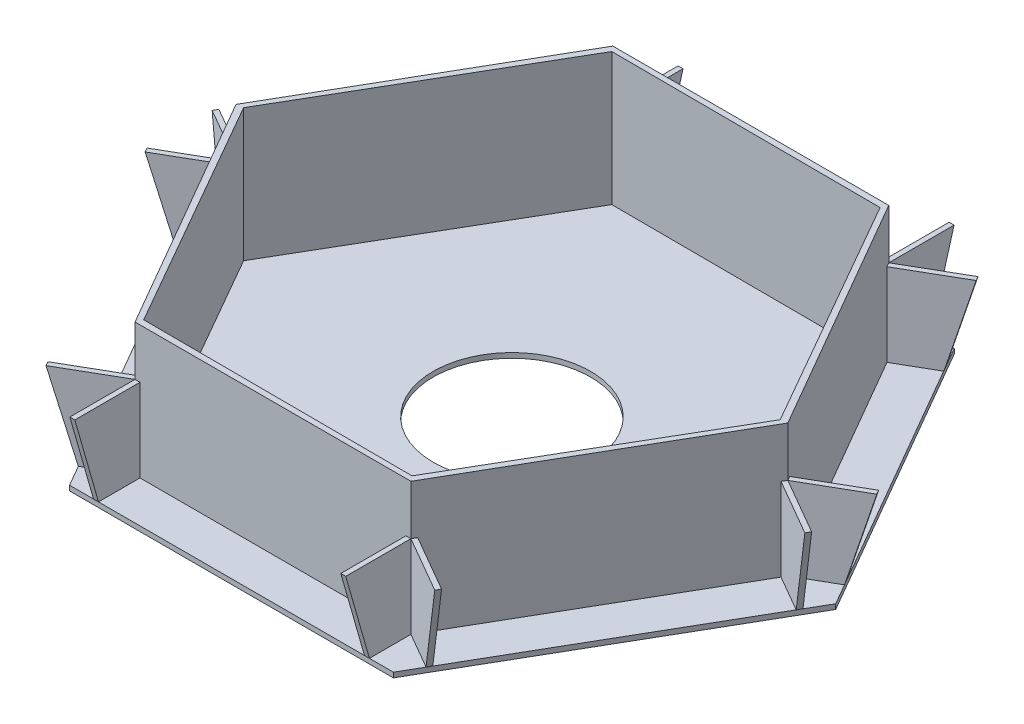
SolidWorks part; units mm, degrees
ref_plane "前视基准面" through (0, 0, 0) normal (0, 0, 1) x (1, 0, 0)
ref_plane "上视基准面" through (0, 0, 0) normal (0, 1, 0) x (1, 0, 0)
ref_plane "右视基准面" through (0, 0, 0) normal (1, 0, 0) x (0, 0, -1)
other "Configuration Table"
sketch "草图3" plane through (0, 0, 0) normal (0, 1, 0) x (1, 0, 0)
  line L1 (195.4, 0) -> (97.7, 169.2214)
  line L2 (97.7, 169.2214) -> (-97.7, 169.2214)
  line L3 (-97.7, 169.2214) -> (-195.4, 0)
  line L4 (-195.4, 0) -> (-97.7, -169.2214)
  line L5 (-97.7, -169.2214) -> (97.7, -169.2214)
  line L6 (97.7, -169.2214) -> (195.4, 0)
  circle A0 centre (0, 0) radius 169.2214 construction
  dimension "D1" = 195.4
extrude "凸台-拉伸2" add sketch "草图3" along normal blind 3
sketch "草图4" plane through (0, 3, 0) normal (0, 1, 0) x (1, 0, 0)
  circle A0 centre (0, 0) radius 47.5
  dimension "D1" = 95
extrude "切除-拉伸1" cut sketch "草图4" against normal blind 3
sketch "草图5" plane through (0, 3, 0) normal (0, 1, 0) x (1, 0, 0)
  line L1 (83.24, 144.1759) -> (-83.24, 144.1759)
  line L2 (-83.24, 144.1759) -> (-166.48, 0)
  line L3 (-166.48, 0) -> (-83.24, -144.1759)
  line L4 (-83.24, -144.1759) -> (83.24, -144.1759)
  line L5 (83.24, -144.1759) -> (166.48, 0)
  line L6 (166.48, 0) -> (83.24, 144.1759)
  line L7 (-80.7295, 141.0053) -> (-162.4789, 0.5888)
  line L8 (-162.4789, 0.5888) -> (-81.7494, -140.4165)
  line L9 (-81.7494, -140.4165) -> (80.7295, -141.0053)
  line L10 (80.7295, -141.0053) -> (162.4789, -0.5888)
  line L11 (162.4789, -0.5888) -> (81.7494, 140.4165)
  line L12 (81.7494, 140.4165) -> (-80.7295, 141.0053)
  circle A0 centre (0, 0) radius 144.1759 construction
  circle A1 centre (0, 0) radius 140.7118 construction
  dimension "D1" = 166.48
  dimension "D2" = 166.48
  dimension "D3" = 162.48
extrude "凸台-拉伸3" add sketch "草图5" along normal blind 80
ref_plane "基准面2" through (0, 3, 0) normal (0, 1, 0) x (1, 0, 0)
ref_plane "基准面3" through (83.24, 0, 0) normal (1, 0, 0) x (0, 0, -1)
sketch "草图11" plane through (83.24, 0, 0) normal (1, 0, 0) x (0, 0, -1)
  line L0 (144.1759, 3) -> (144.1759, 53)
  line L1 (186.1435, 3) -> (-186.1435, 3) construction
  line L2 (144.1759, 83) -> (144.1759, 3) construction
  line L3 (144.1759, 53) -> (183.5822, 53)
  line L4 (183.5822, 53) -> (169.2994, 3)
  line L5 (169.2994, 3) -> (144.1759, 3)
  dimension "D1" = 50
  dimension "D2" = 25.1235
  dimension "D3" = 52
  dimension "D4" = 39.4063
extrude "凸台-拉伸7" add sketch "草图11" against normal blind 3 contours L3 L4 L5 L0
ref_plane "基准面7" through (-41.62, 0, -72.088) normal (-0.5, 0, -0.866) x (-0.866, 0, 0.5)
sketch "草图15" plane through (-41.62, 0, -72.088) normal (-0.5, 0, -0.866) x (-0.866, 0, 0.5)
  line L0 (-144.1759, 53) -> (-144.1759, 3)
  line L1 (-144.1759, 3) -> (-169.2991, 3)
  line L2 (-169.2991, 3) -> (-183.5819, 53)
  line L3 (-183.5819, 53) -> (-144.1759, 53)
  dimension "D1" = 52
  dimension "D2" = 50
  dimension "D3" = 39.406
extrude "凸台-拉伸11" add sketch "草图15" against normal blind 3 contours L2 L3 L0 L1
sketch "草图17" plane through (-41.62, 0, -72.088) normal (-0.5, 0, -0.866) x (-0.866, 0, 0.5)
  line L2 (144.1759, 3) -> (169.2214, 3)
  line L5 (144.1759, 3) -> (144.1759, 53)
  line L6 (144.1759, 83) -> (144.1759, 3) construction
  line L7 (144.1759, 53) -> (183.5042, 53)
  line L8 (183.5042, 53) -> (169.2214, 3)
  dimension "D1" = 50
  dimension "D2" = 52
  dimension "D3" = 39.3283
extrude "凸台-拉伸12" add sketch "草图17" against normal blind 3
sketch "草图19" plane through (83.24, 0, 0) normal (1, 0, 0) x (0, 0, -1)
  line L5 (-144.1759, 3) -> (-144.1759, 53)
  line L6 (-144.1759, 83) -> (-144.1759, 3) construction
  line L13 (-144.1759, 3) -> (-169.2131, 3)
  line L14 (-169.2131, 3) -> (-183.4959, 53)
  line L15 (-183.4959, 53) -> (-144.1759, 53)
  dimension "D1" = 50
  dimension "D2" = 52
  dimension "D3" = 39.32
extrude "凸台-拉伸13" add sketch "草图19" against normal blind 3
ref_plane "基准面8" through (41.62, 0, -72.088) normal (0.5, 0, -0.866) x (-0.866, 0, -0.5)
ref_plane "基准面9" through (-41.62, 0, 72.088) normal (0.5, 0, -0.866) x (-0.866, 0, -0.5)
ref_plane "基准面10" through (-83.24, 0, 0) normal (1, 0, 0) x (0, 0, -1)
sketch "草图20" plane through (-83.24, 0, 0) normal (1, 0, 0) x (0, 0, -1)
  line L0 (144.1759, 3) -> (144.1759, 53)
  line L1 (144.1759, 83) -> (144.1759, 3) construction
  line L2 (144.1759, 53) -> (183.4959, 53)
  line L3 (144.1759, 3) -> (169.2131, 3)
  line L4 (169.2131, 3) -> (183.4959, 53)
  line L5 (208.9129, 120.2294) -> (208.9129, 70.4623)
  dimension "D1" = 50
  dimension "D2" = 52
  dimension "D3" = 39.32
extrude "凸台-拉伸14" add sketch "草图20" along normal blind 3 contours L4 L2 L0 L3
sketch "草图22" plane through (-83.24, 0, 0) normal (1, 0, 0) x (0, 0, -1)
  line L0 (-144.1759, 53) -> (-144.1759, 3)
  line L1 (-144.1759, 83) -> (-144.1759, 3) construction
  line L2 (-144.1759, 3) -> (-169.2131, 3)
  line L3 (-169.2131, 3) -> (-183.4959, 53)
  line L4 (-183.4959, 53) -> (-144.1759, 53)
  dimension "D1" = 50
  dimension "D2" = 52
  dimension "D3" = 39.32
extrude "凸台-拉伸15" add sketch "草图22" along normal blind 3
sketch "草图23" plane through (-41.62, 0, 72.088) normal (0.5, 0, -0.866) x (-0.866, 0, -0.5)
  line L0 (-144.1759, 53) -> (-144.1759, 3)
  line L1 (-144.1759, 3) -> (-169.0913, 3)
  line L2 (-169.0913, 3) -> (-183.4959, 52.9651)
  line L3 (-183.4959, 52.9651) -> (-144.1759, 53)
  dimension "D1" = 50
  dimension "D2" = 52
  dimension "D3" = 39.32
extrude "凸台-拉伸16" add sketch "草图23" along normal blind 3
sketch "草图24" plane through (41.62, 0, -72.088) normal (0.5, 0, -0.866) x (-0.866, 0, -0.5)
  line L6 (-144.1759, 3) -> (-169.2131, 3)
  line L7 (-144.1759, 3) -> (-144.1759, 53)
  line L8 (-144.1759, 83) -> (-144.1759, 3) construction
  line L9 (-144.1759, 53) -> (-183.4959, 53)
  line L10 (-183.4959, 53) -> (-169.2131, 3)
  dimension "D1" = 50
  dimension "D2" = 52
  dimension "D3" = 39.32
extrude "凸台-拉伸17" add sketch "草图24" against normal blind 3
sketch "草图26" plane through (-41.62, 0, 72.088) normal (0.5, 0, -0.866) x (-0.866, 0, -0.5)
  line L0 (144.1759, 53) -> (144.1759, 3)
  line L1 (144.1759, 53) -> (144.1759, 3) construction
  line L2 (144.1759, 3) -> (169.2131, 3)
  line L3 (169.2131, 3) -> (183.4959, 53)
  line L4 (183.4959, 53) -> (144.1759, 53)
  dimension "D1" = 50
  dimension "D2" = 52
  dimension "D3" = 39.32
extrude "凸台-拉伸18" add sketch "草图26" along normal blind 3
sketch "草图27" plane through (41.62, 0, -72.088) normal (0.5, 0, -0.866) x (-0.866, 0, -0.5)
  line L0 (144.1759, 53) -> (144.1759, 3)
  line L1 (144.1759, 3) -> (169.1375, 3)
  line L2 (169.1375, 3) -> (183.4959, 52.9783)
  line L3 (183.4959, 52.9783) -> (144.1759, 53)
  dimension "D1" = 50
  dimension "D2" = 52
  dimension "D3" = 39.32
extrude "凸台-拉伸19" add sketch "草图27" against normal blind 3
ref_plane "基准面12" through (41.62, 0, 72.088) normal (-0.5, 0, -0.866) x (-0.866, 0, 0.5)
sketch "草图28" plane through (41.62, 0, 72.088) normal (-0.5, 0, -0.866) x (-0.866, 0, 0.5)
  line L0 (144.1759, 53) -> (144.1759, 3)
  line L1 (144.1759, 3) -> (169.2131, 3)
  line L2 (169.2131, 3) -> (183.4959, 53)
  line L3 (183.4959, 53) -> (144.1759, 53)
  dimension "D1" = 50
  dimension "D2" = 52
  dimension "D3" = 39.32
extrude "凸台-拉伸20" add sketch "草图28" along normal blind 3
sketch "草图31" plane through (41.62, 0, 72.088) normal (-0.5, 0, -0.866) x (-0.866, 0, 0.5)
  line L0 (-144.1759, 53) -> (-144.1759, 3)
  line L1 (-144.1759, 3) -> (-169.2131, 3)
  line L2 (-169.2131, 3) -> (-183.4959, 53)
  line L3 (-183.4959, 53) -> (-144.1759, 53)
  dimension "D1" = 50
  dimension "D2" = 52
  dimension "D3" = 39.32
extrude "凸台-拉伸21" add sketch "草图31" along normal blind 3
